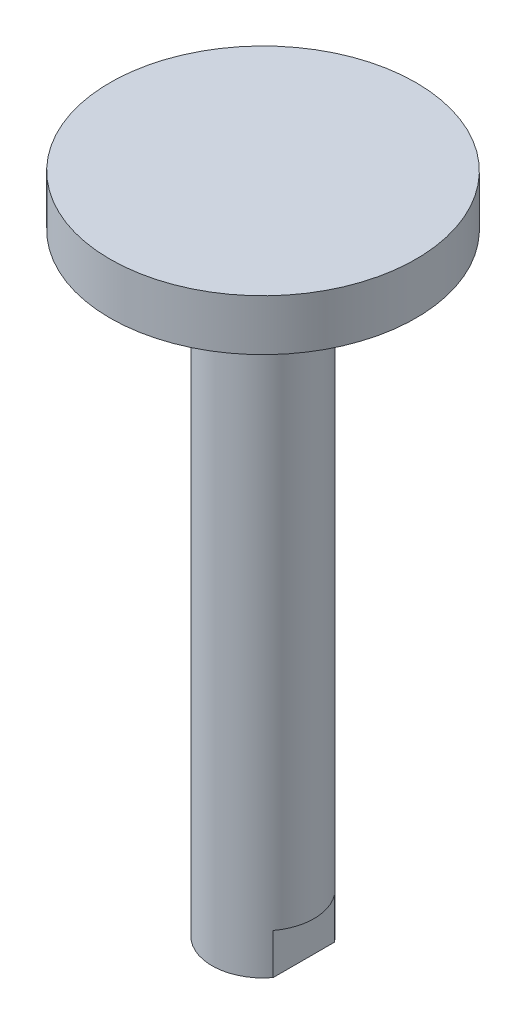
SolidWorks part; units mm, degrees
material "ASTM A36 Aço"
ref_plane "Plano frontal" through (0, 0, 0) normal (0, 0, 1) x (1, 0, 0)
ref_plane "Plano superior" through (0, 0, 0) normal (0, 1, 0) x (1, 0, 0)
ref_plane "Plano direito" through (0, 0, 0) normal (1, 0, 0) x (0, 0, -1)
sketch "Esboço1" plane through (0, 0, 0) normal (0, 0, 1) x (1, 0, 0)
  line L0 (0, 0) -> (-5, 0)
  line L1 (-5, 0) -> (-5, 60)
  line L2 (-5, 60) -> (-15, 60)
  line L3 (-15, 60) -> (-15, 65)
  line L4 (-15, 65) -> (0, 65)
  line L5 (0, 65) -> (0, 0)
  line L6 (0, 0) -> (0, 65) construction
  dimension "D1" = 65
  dimension "D2" = 5
  dimension "D3" = 5
  dimension "D4" = 10
revolve "Revolução1" add sketch "Esboço1" angle 360 about L6
hole_wizard "Broca de rosquear para tarraxa de M51" positions "Esboço5" profile "Esboço7" hole size "M5" standard "ISO"
sketch "Esboço5" plane through (0, 0, 0) normal (0, -1, 0) x (-1, 0, 0)
  point P0 (0, 0)
sketch "Esboço7" plane through (0, 0, 0) normal (1, 0, 0) x (0, 0, -1)
  line L0 (0, 0) -> (0, 11.2618)
  line L1 (0, 11.2618) -> (2.1, 10)
  line L2 (2.1, 10) -> (2.1, 0)
  line L5 (2.1, 0) -> (0, 0)
  line L10 (0, 11.2618) -> (-2.1, 10) construction
  line L11 (0, -6.35) -> (0, 107.95) construction
  dimension "Hole Dia." = 4.2
  dimension "Hole Depth" = 10
  dimension "Drill Angle" = 118
sketch "Esboço8" plane through (0, 0, 0) normal (0, 0, 1) x (1, 0, 0)
  line L0 (4, 0) -> (4, 4)
  line L1 (-5, 0) -> (5, 0) construction
  line L2 (4, 4) -> (5, 4)
  line L3 (5, 0) -> (5, 60) construction
  line L4 (-4, 0) -> (-4, 4)
  line L5 (-4, 4) -> (-5, 4)
  line L6 (-5, 60) -> (-5, 0) construction
  line L7 (-5, 4) -> (-5, 0)
  line L8 (-5, 0) -> (-4, 0)
  line L9 (4, 0) -> (5, 0)
  line L10 (5, 0) -> (5, 4)
  dimension "D1" = 4
  dimension "D2" = 1
extrude "Corte-extrusão1" cut sketch "Esboço8" against normal through all both and the other way through all
